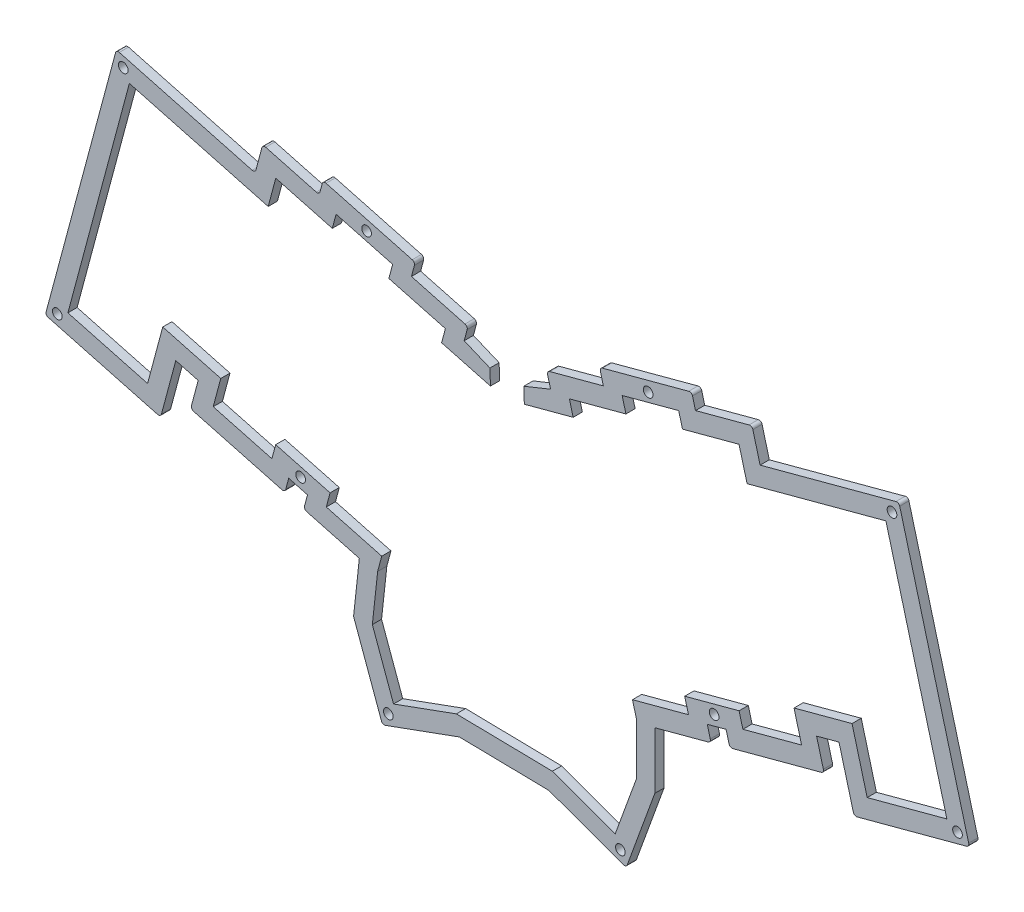
SolidWorks part; units mm, degrees
ref_plane "Front Plane" through (0, 0, 0) normal (0, 0, 1) x (1, 0, 0)
ref_plane "Top Plane" through (0, 0, 0) normal (0, 1, 0) x (1, 0, 0)
ref_plane "Right Plane" through (0, 0, 0) normal (1, 0, 0) x (0, 0, -1)
sketch "Model" plane through (0, 0, 0) normal (0, 0, 1) x (1, 0, 0)
  line L0 (282.165, 226.202) -> (288.4436, 227.8841) construction
  line L1 (267.373, 281.405) -> (273.6516, 283.0871) construction
  line L2 (195.392, 284.0785) -> (194.5766, 287.1211) construction
  line L3 (100.681, 283.685) -> (101.4961, 286.7277) construction
  line L4 (168.22, 168.742) -> (181.234, 164.006) construction
  line L5 (181.234, 164.006) -> (185.972, 177.021) construction
  line L6 (185.972, 177.021) -> (172.956, 181.758) construction
  line L7 (172.956, 181.758) -> (168.22, 168.742) construction
  line L8 (132.176, 184.752) -> (133.281, 181.717) construction
  line L9 (133.281, 181.717) -> (131.706, 181.144) construction
  line L10 (131.706, 181.144) -> (130.099, 185.56) construction
  line L11 (130.099, 185.56) -> (117.085, 180.823) construction
  line L12 (117.085, 180.823) -> (118.692, 176.407) construction
  line L13 (118.692, 176.407) -> (117.118, 175.834) construction
  line L14 (117.118, 175.834) -> (116.013, 178.869) construction
  line L15 (116.013, 178.869) -> (109.812, 176.612) construction
  line L16 (109.812, 176.612) -> (110.917, 173.576) construction
  line L17 (110.917, 173.576) -> (110.141, 173.294) construction
  line L18 (110.141, 173.294) -> (111.048, 170.804) construction
  line L19 (111.048, 170.804) -> (111.822, 171.086) construction
  line L20 (111.822, 171.086) -> (113.968, 165.194) construction
  line L21 (113.968, 165.194) -> (115.588, 165.784) construction
  line L22 (115.588, 165.784) -> (115.999, 164.656) construction
  line L23 (115.999, 164.656) -> (118.959, 165.734) construction
  line L24 (118.959, 165.734) -> (118.549, 166.861) construction
  line L25 (118.549, 166.861) -> (120.169, 167.452) construction
  line L26 (120.169, 167.452) -> (118.641, 171.651) construction
  line L27 (118.641, 171.651) -> (120.215, 172.224) construction
  line L28 (120.215, 172.224) -> (121.821, 167.809) construction
  line L29 (121.821, 167.809) -> (134.837, 172.545) construction
  line L30 (134.837, 172.545) -> (133.23, 176.962) construction
  line L31 (133.23, 176.962) -> (134.804, 177.535) construction
  line L32 (134.804, 177.535) -> (136.332, 173.335) construction
  line L33 (136.332, 173.335) -> (137.953, 173.925) construction
  line L34 (137.953, 173.925) -> (138.363, 172.796) construction
  line L35 (138.363, 172.796) -> (141.323, 173.874) construction
  line L36 (141.323, 173.874) -> (140.913, 175.001) construction
  line L37 (140.913, 175.001) -> (142.533, 175.592) construction
  line L38 (142.533, 175.592) -> (140.389, 181.483) construction
  line L39 (140.389, 181.483) -> (141.165, 181.766) construction
  line L40 (141.165, 181.766) -> (140.258, 184.256) construction
  line L41 (140.258, 184.256) -> (139.484, 183.974) construction
  line L42 (139.484, 183.974) -> (138.378, 187.009) construction
  line L43 (138.378, 187.009) -> (132.176, 184.752) construction
  line L44 (150.319, 175.258) -> (163.333, 170.521) construction
  line L45 (163.333, 170.521) -> (168.071, 183.535) construction
  line L46 (168.071, 183.535) -> (155.055, 188.273) construction
  line L47 (155.055, 188.273) -> (150.319, 175.258) construction
  line L48 (109.952, 197.835) -> (123.33, 194.251) construction
  line L49 (123.33, 194.251) -> (126.916, 207.629) construction
  line L50 (126.916, 207.629) -> (113.537, 211.213) construction
  line L51 (113.537, 211.213) -> (109.952, 197.835) construction
  line L52 (169.157, 208.022) -> (172.741, 194.644) construction
  line L53 (172.741, 194.644) -> (186.119, 198.228) construction
  line L54 (186.119, 198.228) -> (182.535, 211.607) construction
  line L55 (182.535, 211.607) -> (169.157, 208.022) construction
  line L56 (92.7848, 207.366) -> (106.163, 203.781) construction
  line L57 (106.163, 203.781) -> (109.747, 217.159) construction
  line L58 (109.747, 217.159) -> (96.369, 220.744) construction
  line L59 (96.369, 220.744) -> (92.7848, 207.366) construction
  line L60 (186.326, 217.552) -> (189.91, 204.174) construction
  line L61 (189.91, 204.174) -> (203.288, 207.759) construction
  line L62 (203.288, 207.759) -> (199.704, 221.137) construction
  line L63 (199.704, 221.137) -> (186.326, 217.552) construction
  line L64 (114.883, 216.236) -> (128.261, 212.652) construction
  line L65 (128.261, 212.652) -> (131.845, 226.03) construction
  line L66 (131.845, 226.03) -> (118.467, 229.614) construction
  line L67 (118.467, 229.614) -> (114.883, 216.236) construction
  line L68 (164.226, 226.423) -> (167.812, 213.045) construction
  line L69 (167.812, 213.045) -> (181.19, 216.629) construction
  line L70 (181.19, 216.629) -> (177.604, 230.007) construction
  line L71 (177.604, 230.007) -> (164.226, 226.423) construction
  line L72 (75.6158, 216.896) -> (88.9938, 213.312) construction
  line L73 (88.9938, 213.312) -> (92.5781, 226.69) construction
  line L74 (92.5781, 226.69) -> (79.2, 230.274) construction
  line L75 (79.2, 230.274) -> (75.6158, 216.896) construction
  line L76 (55.9827, 217.227) -> (69.3607, 213.643) construction
  line L77 (69.3607, 213.643) -> (72.9449, 227.021) construction
  line L78 (72.9449, 227.021) -> (59.5672, 230.605) construction
  line L79 (59.5672, 230.605) -> (55.9827, 217.227) construction
  line L80 (203.494, 227.083) -> (207.078, 213.705) construction
  line L81 (207.078, 213.705) -> (220.457, 217.29) construction
  line L82 (220.457, 217.29) -> (216.872, 230.668) construction
  line L83 (216.872, 230.668) -> (203.494, 227.083) construction
  line L84 (223.128, 227.414) -> (226.712, 214.036) construction
  line L85 (226.712, 214.036) -> (240.09, 217.62) construction
  line L86 (240.09, 217.62) -> (236.506, 230.998) construction
  line L87 (236.506, 230.998) -> (223.128, 227.414) construction
  line L88 (12.1157, 219.121) -> (25.4937, 215.536) construction
  line L89 (25.4937, 215.536) -> (29.078, 228.914) construction
  line L90 (29.078, 228.914) -> (15.7, 232.499) construction
  line L91 (15.7, 232.499) -> (12.1157, 219.121) construction
  line L92 (266.995, 229.307) -> (270.579, 215.929) construction
  line L93 (270.579, 215.929) -> (283.957, 219.513) construction
  line L94 (283.957, 219.513) -> (280.373, 232.891) construction
  line L95 (280.373, 232.891) -> (266.995, 229.307) construction
  line L96 (97.7138, 225.767) -> (111.092, 222.183) construction
  line L97 (111.092, 222.183) -> (114.677, 235.56) construction
  line L98 (114.677, 235.56) -> (101.299, 239.145) construction
  line L99 (101.299, 239.145) -> (97.7138, 225.767) construction
  line L100 (181.394, 235.953) -> (184.98, 222.575) construction
  line L101 (184.98, 222.575) -> (198.357, 226.159) construction
  line L102 (198.357, 226.159) -> (194.773, 239.538) construction
  line L103 (194.773, 239.538) -> (181.394, 235.953) construction
  line L104 (40.0473, 231.357) -> (53.425, 227.773) construction
  line L105 (53.425, 227.773) -> (57.0096, 241.151) construction
  line L106 (57.0096, 241.151) -> (43.6316, 244.735) construction
  line L107 (43.6316, 244.735) -> (40.0473, 231.357) construction
  line L108 (239.062, 241.545) -> (242.648, 228.166) construction
  line L109 (242.648, 228.166) -> (256.024, 231.75) construction
  line L110 (256.024, 231.75) -> (252.44, 245.128) construction
  line L111 (252.44, 245.128) -> (239.062, 241.545) construction
  line L112 (119.814, 234.637) -> (133.192, 231.053) construction
  line L113 (133.192, 231.053) -> (136.776, 244.431) construction
  line L114 (136.776, 244.431) -> (123.396, 248.015) construction
  line L115 (123.396, 248.015) -> (119.814, 234.637) construction
  line L116 (159.297, 244.824) -> (162.88, 231.445) construction
  line L117 (162.88, 231.445) -> (176.258, 235.03) construction
  line L118 (176.258, 235.03) -> (172.675, 248.408) construction
  line L119 (172.675, 248.408) -> (159.297, 244.824) construction
  line L120 (80.5462, 235.297) -> (93.9243, 231.713) construction
  line L121 (93.9243, 231.713) -> (97.5099, 245.091) construction
  line L122 (97.5099, 245.091) -> (84.1304, 248.675) construction
  line L123 (84.1304, 248.675) -> (80.5462, 235.297) construction
  line L124 (60.912, 235.628) -> (74.2901, 232.044) construction
  line L125 (74.2901, 232.044) -> (77.8757, 245.422) construction
  line L126 (77.8757, 245.422) -> (64.4977, 249.006) construction
  line L127 (64.4977, 249.006) -> (60.912, 235.628) construction
  line L128 (198.563, 245.484) -> (202.147, 232.106) construction
  line L129 (202.147, 232.106) -> (215.525, 235.692) construction
  line L130 (215.525, 235.692) -> (211.941, 249.069) construction
  line L131 (211.941, 249.069) -> (198.563, 245.484) construction
  line L132 (218.196, 245.814) -> (221.782, 232.436) construction
  line L133 (221.782, 232.436) -> (235.16, 236.021) construction
  line L134 (235.16, 236.021) -> (231.574, 249.399) construction
  line L135 (231.574, 249.399) -> (218.196, 245.814) construction
  line L136 (17.045, 237.521) -> (30.423, 233.937) construction
  line L137 (30.423, 233.937) -> (34.0086, 247.315) construction
  line L138 (34.0086, 247.315) -> (20.6306, 250.899) construction
  line L139 (20.6306, 250.899) -> (17.045, 237.521) construction
  line L140 (262.063, 247.708) -> (265.649, 234.33) construction
  line L141 (265.649, 234.33) -> (279.026, 237.914) construction
  line L142 (279.026, 237.914) -> (275.442, 251.292) construction
  line L143 (275.442, 251.292) -> (262.063, 247.708) construction
  line L144 (102.646, 244.168) -> (116.024, 240.584) construction
  line L145 (116.024, 240.584) -> (119.607, 253.962) construction
  line L146 (119.607, 253.962) -> (106.229, 257.546) construction
  line L147 (106.229, 257.546) -> (102.646, 244.168) construction
  line L148 (176.465, 254.354) -> (180.049, 240.976) construction
  line L149 (180.049, 240.976) -> (193.427, 244.56) construction
  line L150 (193.427, 244.56) -> (189.843, 257.938) construction
  line L151 (189.843, 257.938) -> (176.465, 254.354) construction
  line L152 (44.9778, 249.759) -> (58.3558, 246.174) construction
  line L153 (58.3558, 246.174) -> (61.94, 259.553) construction
  line L154 (61.94, 259.553) -> (48.562, 263.136) construction
  line L155 (48.562, 263.136) -> (44.9778, 249.759) construction
  line L156 (234.133, 259.945) -> (237.717, 246.567) construction
  line L157 (237.717, 246.567) -> (251.095, 250.151) construction
  line L158 (251.095, 250.151) -> (247.511, 263.529) construction
  line L159 (247.511, 263.529) -> (234.133, 259.945) construction
  line L160 (124.743, 253.038) -> (138.122, 249.454) construction
  line L161 (138.122, 249.454) -> (141.707, 262.832) construction
  line L162 (141.707, 262.832) -> (128.329, 266.416) construction
  line L163 (128.329, 266.416) -> (124.743, 253.038) construction
  line L164 (154.365, 263.224) -> (157.951, 249.845) construction
  line L165 (157.951, 249.845) -> (171.329, 253.432) construction
  line L166 (171.329, 253.432) -> (167.743, 266.809) construction
  line L167 (167.743, 266.809) -> (154.365, 263.224) construction
  line L168 (85.477, 253.699) -> (98.855, 250.114) construction
  line L169 (98.855, 250.114) -> (102.439, 263.492) construction
  line L170 (102.439, 263.492) -> (89.0612, 267.076) construction
  line L171 (89.0612, 267.076) -> (85.477, 253.699) construction
  line L172 (65.8442, 254.03) -> (79.2219, 250.443) construction
  line L173 (79.2219, 250.443) -> (82.8065, 263.823) construction
  line L174 (82.8065, 263.823) -> (69.427, 267.407) construction
  line L175 (69.427, 267.407) -> (65.8442, 254.03) construction
  line L176 (193.632, 263.885) -> (197.218, 250.507) construction
  line L177 (197.218, 250.507) -> (210.596, 254.092) construction
  line L178 (210.596, 254.092) -> (207.01, 267.47) construction
  line L179 (207.01, 267.47) -> (193.632, 263.885) construction
  line L180 (213.267, 264.215) -> (216.851, 250.837) construction
  line L181 (216.851, 250.837) -> (230.229, 254.422) construction
  line L182 (230.229, 254.422) -> (226.645, 267.8) construction
  line L183 (226.645, 267.8) -> (213.267, 264.215) construction
  line L184 (21.977, 255.922) -> (35.355, 252.338) construction
  line L185 (35.355, 252.338) -> (38.9378, 265.716) construction
  line L186 (38.9378, 265.716) -> (25.5598, 269.3) construction
  line L187 (25.5598, 269.3) -> (21.977, 255.922) construction
  line L188 (257.132, 266.109) -> (260.718, 252.729) construction
  line L189 (260.718, 252.729) -> (274.096, 256.315) construction
  line L190 (274.096, 256.315) -> (270.512, 269.693) construction
  line L191 (270.512, 269.693) -> (257.132, 266.109) construction
  line L192 (107.575, 262.569) -> (120.953, 258.984) construction
  line L193 (120.953, 258.984) -> (124.539, 272.362) construction
  line L194 (124.539, 272.362) -> (111.161, 275.947) construction
  line L195 (111.161, 275.947) -> (107.575, 262.569) construction
  line L196 (171.534, 272.755) -> (175.118, 259.377) construction
  line L197 (175.118, 259.377) -> (188.496, 262.961) construction
  line L198 (188.496, 262.961) -> (184.912, 276.339) construction
  line L199 (184.912, 276.339) -> (171.534, 272.755) construction
  line L200 (49.9071, 268.159) -> (63.2852, 264.575) construction
  line L201 (63.2852, 264.575) -> (66.8708, 277.953) construction
  line L202 (66.8708, 277.953) -> (53.4928, 281.537) construction
  line L203 (53.4928, 281.537) -> (49.9071, 268.159) construction
  line L204 (229.201, 278.346) -> (232.786, 264.968) construction
  line L205 (232.786, 264.968) -> (246.164, 268.554) construction
  line L206 (246.164, 268.554) -> (242.579, 281.932) construction
  line L207 (242.579, 281.932) -> (229.201, 278.346) construction
  line L208 (90.4074, 272.099) -> (103.785, 268.515) construction
  line L209 (103.785, 268.515) -> (107.37, 281.893) construction
  line L210 (107.37, 281.893) -> (93.992, 285.477) construction
  line L211 (93.992, 285.477) -> (90.4074, 272.099) construction
  line L212 (70.7732, 272.43) -> (84.1513, 268.844) construction
  line L213 (84.1513, 268.844) -> (87.7369, 282.222) construction
  line L214 (87.7369, 282.222) -> (74.3589, 285.808) construction
  line L215 (74.3589, 285.808) -> (70.7732, 272.43) construction
  line L216 (188.703, 282.286) -> (192.286, 268.908) construction
  line L217 (192.286, 268.908) -> (205.664, 272.493) construction
  line L218 (205.664, 272.493) -> (202.081, 285.871) construction
  line L219 (202.081, 285.871) -> (188.703, 282.286) construction
  line L220 (208.336, 282.616) -> (211.92, 269.238) construction
  line L221 (211.92, 269.238) -> (225.298, 272.822) construction
  line L222 (225.298, 272.822) -> (221.714, 286.2) construction
  line L223 (221.714, 286.2) -> (208.336, 282.616) construction
  line L224 (26.9062, 274.323) -> (40.284, 270.739) construction
  line L225 (40.284, 270.739) -> (43.8697, 284.117) construction
  line L226 (43.8697, 284.117) -> (30.4919, 287.701) construction
  line L227 (30.4919, 287.701) -> (26.9062, 274.323) construction
  line L228 (252.203, 284.508) -> (255.786, 271.131) construction
  line L229 (255.786, 271.131) -> (269.165, 274.716) construction
  line L230 (269.165, 274.716) -> (265.581, 288.094) construction
  line L231 (265.581, 288.094) -> (252.203, 284.508) construction
  line L232 (37.1808, 285.909) -> (37.996, 288.9517) construction
  line L233 (28.6991, 281.012) -> (22.4207, 282.6948) construction
  line L234 (18.8047, 217.3285) -> (17.9893, 214.2859) construction
  line L235 (13.9078, 225.81) -> (7.6293, 227.4922) construction
  line L236 (277.268, 217.721) -> (278.0831, 214.6783) construction
  line L237 (271.2035, 292.2232) -> (291.0512, 218.1525)
  line L238 (241.3027, 224.5444) -> (243.7675, 215.3441)
  line L239 (81.0479, 284.015) -> (81.8635, 287.0576) construction
  line L240 (181.234, 164.006) -> (184.194, 162.9285) construction
  line L241 (91.0631, 284.5916) -> (72.6639, 289.5236)
  line L242 (117.85, 274.1545) -> (118.6654, 277.1971) construction
  line L243 (135.018, 264.624) -> (135.8331, 267.6667) construction
  line L244 (161.054, 265.0165) -> (160.2386, 268.0591) construction
  line L245 (178.223, 274.547) -> (177.4079, 277.5897) construction
  line L246 (215.025, 284.408) -> (214.2099, 287.4507) construction
  line L247 (258.892, 286.301) -> (258.2357, 288.7493) construction
  line L248 (196.599, 205.9665) -> (197.4144, 202.9239) construction
  line L249 (92.2965, 289.1937) -> (110.6958, 284.2617)
  line L250 (213.7675, 215.4975) -> (214.5828, 212.4548) construction
  line L251 (233.401, 215.828) -> (234.2161, 212.7853) construction
  line L252 (62.6717, 215.435) -> (61.8566, 212.3923) construction
  line L253 (82.3048, 215.104) -> (81.4897, 212.0613) construction
  line L254 (99.4739, 205.5735) -> (98.6586, 202.5309) construction
  line L255 (35.8867, 229.2106) -> (54.7701, 224.1516)
  line L256 (60.1818, 279.745) -> (60.9969, 282.7877) construction
  line L257 (72.6639, 289.5236) -> (70.1982, 280.3232)
  line L258 (105.8147, 195.273) -> (104.0964, 179.4507)
  line L259 (52.3052, 214.9511) -> (54.7701, 224.1516)
  line L260 (260.1862, 229.6041) -> (265.1156, 211.2042)
  line L261 (203.777, 289.5866) -> (185.3762, 284.6556)
  line L262 (30.9571, 210.8115) -> (35.8867, 229.2106)
  line L263 (141.707, 262.832) -> (142.5224, 265.8746) construction
  line L264 (154.365, 263.224) -> (153.5495, 266.2666) construction
  line L265 (181.234, 164.006) -> (180.1565, 161.046) construction
  line L266 (92.2965, 289.1937) -> (91.0631, 284.5916)
  line L267 (169.4396, 270.5248) -> (150.6904, 265.5004) construction
  line L268 (110.6958, 284.2617) -> (109.4634, 279.6637)
  line L269 (127.8626, 274.7318) -> (126.6303, 270.1341)
  line L270 (127.8626, 274.7318) -> (109.4634, 279.6637)
  line L271 (260.1862, 229.6041) -> (241.3027, 224.5444)
  line L272 (126.6303, 270.1341) -> (145.3813, 265.1084) construction
  line L273 (185.3762, 284.6556) -> (186.6084, 280.0546)
  line L274 (142.3447, 270.8715) -> (142.5224, 265.8746)
  line L275 (203.777, 289.5866) -> (205.0099, 284.986)
  line L276 (168.2073, 275.1248) -> (169.4396, 270.5248)
  line L277 (205.0099, 284.986) -> (223.4098, 289.9154)
  line L278 (223.4098, 289.9154) -> (226.0333, 280.1226)
  line L279 (186.6084, 280.0546) -> (168.2073, 275.1248)
  line L280 (104.0964, 179.4507) -> (110.9864, 160.5147)
  line L281 (152.687, 181.7655) -> (183.603, 170.5135) construction
  line L282 (110.5015, 171.0598) -> (141.4185, 182.3092) construction
  line L283 (27.2858, 222.225) -> (33.5644, 220.5428) construction
  line L284 (90.3394, 209.6904) -> (72.6399, 214.4322)
  line L285 (71.4079, 209.8335) -> (72.6399, 214.4322)
  line L286 (89.1069, 205.0898) -> (90.3394, 209.6904)
  line L287 (89.1069, 205.0898) -> (107.1497, 200.256)
  line L288 (107.1497, 200.256) -> (105.8147, 195.273)
  line L289 (110.9864, 160.5147) -> (131.4289, 167.9529)
  line L290 (71.4079, 209.8335) -> (52.3052, 214.9511)
  line L291 (5.0216, 217.7602) -> (25.0282, 292.4264)
  line L292 (130.099, 185.56) -> (121.821, 167.809) construction
  line L293 (190.0384, 195.7708) -> (190.0096, 178.9037)
  line L294 (235.89, 280.139) -> (235.2337, 282.5873) construction
  line L295 (162.6744, 167.408) -> (183.1165, 159.9688)
  line L296 (131.4289, 167.9529) -> (162.6744, 167.408)
  line L297 (5.0216, 217.7602) -> (30.9571, 210.8115)
  line L298 (46.7361, 229.565) -> (45.921, 226.5223) construction
  line L299 (265.1156, 211.2042) -> (291.0512, 218.1525)
  line L300 (25.0282, 292.4264) -> (70.1982, 280.3232)
  line L301 (226.0333, 280.1226) -> (271.2035, 292.2232)
  line L302 (216.1359, 206.6593) -> (215.3122, 209.7329) construction
  line L303 (128.329, 170.177) -> (129.4061, 167.2169) construction
  line L304 (249.336, 229.958) -> (250.1513, 226.9153) construction
  line L305 (268.787, 222.618) -> (262.5084, 220.9359) construction
  line L306 (109.952, 197.835) -> (106.7322, 198.6976) construction
  line L307 (-2.3268, 213.5174) -> (20.7855, 299.7748)
  line L308 (186.119, 198.228) -> (189.1617, 199.0431) construction
  line L309 (206.9661, 205.4835) -> (188.7445, 200.6005)
  line L310 (188.7445, 200.6005) -> (190.0384, 195.7708)
  line L311 (20.7855, 299.7748) -> (65.9558, 287.6716)
  line L312 (68.4216, 296.8725) -> (65.9558, 287.6716)
  line L313 (86.821, 291.9405) -> (68.4216, 296.8725)
  line L314 (88.0544, 296.5426) -> (86.821, 291.9405)
  line L315 (88.0544, 296.5426) -> (118.0445, 288.5037)
  line L316 (118.0445, 288.5037) -> (116.8121, 283.9057)
  line L317 (135.2113, 278.9738) -> (116.8121, 283.9057)
  line L318 (135.2113, 278.9738) -> (133.9791, 274.3762)
  line L319 (133.9791, 274.3762) -> (142.3447, 270.8715)
  line L320 (153.3718, 271.2635) -> (162.0915, 274.7674)
  line L321 (20.7855, 299.7748) -> (25.0282, 292.4264) construction
  line L322 (160.859, 279.3678) -> (162.0915, 274.7674)
  line L323 (179.2607, 284.2977) -> (160.859, 279.3678)
  line L324 (178.0286, 288.8984) -> (179.2607, 284.2977)
  line L325 (208.0195, 296.9352) -> (178.0286, 288.8984)
  line L326 (208.0195, 296.9352) -> (209.2525, 292.3342)
  line L327 (209.2525, 292.3342) -> (227.6528, 297.2637)
  line L328 (227.6528, 297.2637) -> (230.2763, 287.4708)
  line L329 (230.2763, 287.4708) -> (275.4462, 299.5713)
  line L330 (298.3998, 213.9096) -> (294.5027, 216.1597) construction
  line L331 (275.4462, 299.5713) -> (298.3998, 213.9096)
  line L332 (260.8726, 203.856) -> (298.3998, 213.9096)
  line L333 (255.9433, 222.2556) -> (260.8726, 203.856)
  line L334 (255.9433, 222.2556) -> (248.6509, 220.3017)
  line L335 (183.1165, 159.9688) -> (190.0096, 178.9037)
  line L336 (248.6509, 220.3017) -> (251.1158, 211.1012)
  line L337 (220.4222, 202.8783) -> (251.1158, 211.1012)
  line L338 (219.1898, 207.4775) -> (220.4222, 202.8783)
  line L339 (213.082, 205.8412) -> (219.1898, 207.4775)
  line L340 (206.9661, 205.4835) -> (205.7333, 210.084)
  line L341 (223.4323, 214.8256) -> (224.6648, 210.2265)
  line L342 (205.7333, 210.084) -> (223.4323, 214.8256)
  line L343 (214.3147, 201.2411) -> (213.082, 205.8412)
  line L344 (214.3147, 201.2411) -> (196.0393, 196.3437)
  line L345 (224.6648, 210.2265) -> (243.7675, 215.3441)
  line L346 (196.0393, 196.3437) -> (196.0078, 177.8406)
  line L347 (150.6904, 265.5004) -> (170.7656, 190.6076) construction
  line L348 (186.7023, 152.2789) -> (196.0078, 177.8406)
  line L349 (161.566, 161.4264) -> (186.7023, 152.2789)
  line L350 (132.4358, 161.9344) -> (161.566, 161.4264)
  line L351 (107.3996, 152.8248) -> (132.4358, 161.9344)
  line L352 (97.9807, 178.7109) -> (107.3996, 152.8248)
  line L353 (99.8582, 195.9979) -> (97.9807, 178.7109)
  line L354 (141.707, 262.832) -> (154.365, 263.224) construction
  line L355 (81.7586, 200.8468) -> (99.8582, 195.9979)
  line L356 (81.7586, 200.8468) -> (82.9911, 205.4475)
  line L357 (82.9911, 205.4475) -> (76.8829, 207.0839)
  line L358 (75.6509, 202.4852) -> (76.8829, 207.0839)
  line L359 (75.6509, 202.4852) -> (44.9569, 210.7082)
  line L360 (44.9569, 210.7082) -> (47.4218, 219.9086)
  line L361 (40.1295, 221.8623) -> (47.4218, 219.9086)
  line L362 (35.1999, 203.4631) -> (40.1295, 221.8623)
  line L363 (-2.3268, 213.5174) -> (35.1999, 203.4631)
  line L364 (20.7855, 299.7748) -> (23.0356, 295.8777) construction
  line L365 (142.5224, 265.8746) -> (153.5495, 266.2666) construction
  line L366 (275.4462, 299.5713) -> (271.2035, 292.2232) construction
  line L367 (291.0512, 218.1525) -> (298.3998, 213.9096) construction
  line L368 (-2.3268, 213.5174) -> (5.0216, 217.7602) construction
  line L369 (107.3996, 152.8248) -> (110.9864, 160.5147) construction
  line L370 (183.1165, 159.9688) -> (186.7023, 152.2789) construction
  line L371 (107.3996, 152.8248) -> (109.3018, 156.903) construction
  line L372 (184.8006, 156.3573) -> (186.7023, 152.2789) construction
  line L373 (106.163, 203.781) -> (189.91, 204.174) construction
  line L374 (101.4961, 286.7277) -> (103.0495, 292.5232) construction
  line L375 (194.5766, 287.1211) -> (193.0241, 292.9168) construction
  line L376 (23.0356, 295.8777) -> (23.8591, 298.9513) construction
  line L377 (193.0241, 292.9168) -> (193.8474, 289.8432) construction
  line L378 (214.5828, 212.4548) -> (216.1359, 206.6593) construction
  line L379 (103.0495, 292.5232) -> (102.2257, 289.4497) construction
  line L380 (275.4462, 299.5713) -> (273.1961, 295.6743) construction
  line L381 (-2.3268, 213.5174) -> (1.5702, 215.7675) construction
  line L382 (81.4897, 212.0613) -> (79.937, 206.2657) construction
  line L383 (81.4897, 212.0613) -> (79.937, 206.2657) construction
  line L384 (214.5828, 212.4548) -> (216.1359, 206.6593) construction
  line L385 (145.3813, 265.1084) -> (125.265, 190.0622) construction
  line L386 (190.0384, 195.7708) -> (170.7656, 190.6076) construction
  line L387 (148.0359, 266.0706) -> (148.0365, 203.9775) construction
  line L388 (105.8147, 195.273) -> (125.265, 190.0622) construction
  line L389 (104.0964, 179.4507) -> (140.9309, 192.8582) construction
  line L390 (190.0096, 178.9037) -> (153.1726, 192.3111) construction
  line L391 (152.687, 181.7655) -> (149.727, 182.8428) construction
  line L392 (131.4289, 167.9529) -> (146.3042, 173.3654) construction
  line L393 (153.1726, 192.3111) -> (147.152, 175.767) construction
  line L394 (146.3042, 173.3654) -> (162.6744, 167.408) construction
  line L395 (141.4185, 182.3092) -> (144.3786, 183.3863) construction
  line L396 (147.152, 175.767) -> (140.9309, 192.8582) construction
  line L397 (110.5015, 171.0598) -> (107.5414, 169.9827) construction
  line L398 (123.592, 183.1915) -> (122.5136, 186.1545) construction
  line L399 (105.8147, 195.273) -> (183.187, 229.264) construction
  line L400 (171.073, 185.7954) -> (164.1828, 166.8591) construction
  line L401 (112.8845, 228.8715) -> (190.0384, 195.7708) construction
  line L402 (105.8147, 195.273) -> (133.2811, 207.3395) construction
  line L403 (162.4685, 207.5989) -> (190.0384, 195.7708) construction
  line L404 (136.776, 244.431) -> (159.297, 244.824) construction
  line L405 (136.776, 244.431) -> (142.5224, 244.5313) construction
  line L406 (159.297, 244.824) -> (153.5495, 244.7237) construction
  line L407 (79.937, 206.2657) -> (80.7604, 209.3393) construction
  line L408 (153.3718, 271.2635) -> (153.5495, 266.2666)
  line L409 (126.6303, 270.1341) -> (142.5224, 265.8746)
  line L410 (153.5495, 266.2666) -> (169.4396, 270.5248)
  line L425 (164.1828, 166.8591) -> (183.1165, 159.9688) construction
  line L426 (190.0096, 178.9037) -> (171.073, 185.7954) construction
  line L427 (99.8582, 195.9979) -> (99.8582, 195.9979) construction
  line L428 (99.8582, 195.9979) -> (97.9807, 178.7109) construction
  line L429 (150.6904, 265.5004) -> (145.3813, 265.1084) construction
  line L430 (149.6841, 271.4425) -> (145.9529, 271.1669) construction
  line L431 (133.9791, 274.3762) -> (145.9529, 271.1669) construction
  line L432 (162.0915, 274.7674) -> (149.6841, 271.4425) construction
  line L433 (256.6831, 294.5449) -> (275.4462, 299.5713) construction
  line L434 (230.2763, 287.4708) -> (256.6831, 294.5449) construction
  line L435 (196.0393, 196.3437) -> (196.0393, 196.3437) construction
  line L436 (196.0393, 196.3437) -> (196.0078, 177.8406) construction
  line L437 (226.0333, 280.1226) -> (258.2357, 288.7493) construction
  line L438 (258.2357, 288.7493) -> (271.2035, 292.2232) construction
  circle A0 centre (23.0356, 295.8777) radius 1.575
  circle A1 centre (109.3018, 156.903) radius 1.575
  circle A2 centre (184.8006, 156.3573) radius 1.575
  circle A3 centre (193.8474, 289.8432) radius 1.575
  circle A4 centre (102.2257, 289.4497) radius 1.575
  circle A5 centre (273.1961, 295.6743) radius 1.575
  circle A6 centre (1.5702, 215.7675) radius 1.575
  circle A7 centre (294.5027, 216.1597) radius 1.575
  circle A8 centre (80.7604, 209.3393) radius 1.575
  circle A9 centre (215.3122, 209.7329) radius 1.575
  circle A10 centre (133.2811, 207.3395) radius 1.575 construction
  circle A11 centre (162.4685, 207.5989) radius 1.575 construction
  circle A12 centre (142.5224, 244.5313) radius 1.575 construction
  circle A13 centre (153.5495, 244.7237) radius 1.575 construction
  point P253 (61.8566, 212.3923)
  point P289 (81.8635, 287.0576)
  point P293 (194.5766, 287.1211)
  point P295 (101.4961, 286.7277)
  point P297 (81.4897, 212.0613)
  point P361 (125.96, 176.6845)
  point P362 (125.96, 176.6845)
  point P374 (214.5828, 212.4548)
  point P377 (234.2161, 212.7853)
  point P378 (177.4079, 277.5897)
  point P386 (214.2099, 287.4507)
  dimension "D5" = 6
  dimension "D4" = 3.15
  dimension "D7" = 30.011
  dimension "D8" = 30
  dimension "D1" = 9.5249
  dimension "D2" = 6.5
  dimension "D6" = 4.5
  dimension "D10" = 4.5
extrude "Boss-Extrude1" add sketch "Model" against normal blind 3
fillet "Fillet1" radius 1 24 edges at (35.1999, 203.4631, -1.5) (44.9569, 210.7082, -1.5) (75.6509, 202.4852, -1.5) (81.7586, 200.8468, -1.5) (107.3996, 152.8248, -1.5) (186.7023, 152.2789, -1.5) (214.3147, 201.2411, -1.5) (220.4222, 202.8783, -1.5) (260.8726, 203.856, -1.5) (251.1158, 211.1012, -1.5) (298.3998, 213.9096, -1.5) (275.4462, 299.5713, -1.5) (227.6528, 297.2637, -1.5) (208.0195, 296.9352, -1.5) (178.0286, 288.8984, -1.5) (160.859, 279.3678, -1.5) (88.0544, 296.5426, -1.5) (135.2113, 278.9738, -1.5) (118.0445, 288.5037, -1.5) (86.821, 291.9405, -1.5) (65.9558, 287.6716, -1.5) (68.4216, 296.8725, -1.5) (20.7855, 299.7748, -1.5) (-2.3268, 213.5174, -1.5)
